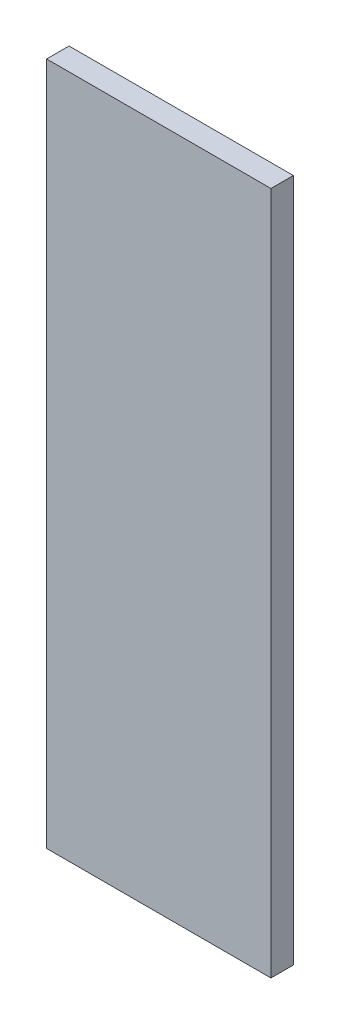
SolidWorks part; units mm, degrees
ref_plane "Front Plane" through (0, 0, 0) normal (0, 0, 1) x (1, 0, 0)
ref_plane "Top Plane" through (0, 0, 0) normal (0, 1, 0) x (1, 0, 0)
ref_plane "Right Plane" through (0, 0, 0) normal (1, 0, 0) x (0, 0, -1)
sketch "Sketch1" plane through (0, 0, 0) normal (0, 0, 1) x (1, 0, 0)
  line L1 (0, 0) -> (100, 0)
  line L2 (0, 0) -> (0, 304.8)
  line L3 (0, 304.8) -> (100, 304.8)
  line L4 (100, 0) -> (100, 304.8)
  dimension "D1" = 100
  dimension "D2" = 304.8
extrude "Boss-Extrude1" add sketch "Sketch1" along normal blind 10
